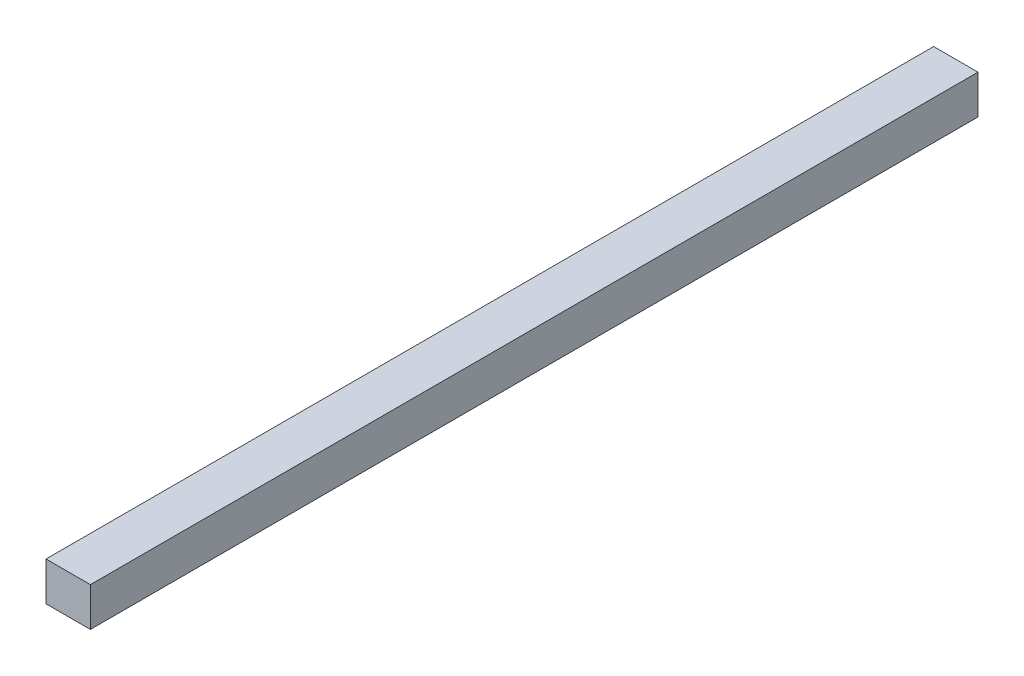
SolidWorks part; units mm, degrees
ref_plane "Front Plane" through (0, 0, 0) normal (0, 0, 1) x (1, 0, 0)
ref_plane "Top Plane" through (0, 0, 0) normal (0, 1, 0) x (1, 0, 0)
ref_plane "Right Plane" through (0, 0, 0) normal (1, 0, 0) x (0, 0, -1)
sketch "Sketch1" plane through (0, 0, 0) normal (0, 1, 0) x (1, 0, 0)
  line L1 (32.4965, 34.4965) -> (34.4965, 34.4965)
  line L2 (32.4965, 34.4965) -> (32.4965, -5.5035)
  line L3 (32.4965, -5.5035) -> (34.4965, -5.5035)
  line L4 (34.4965, 34.4965) -> (34.4965, -5.5035)
  dimension "D1" = 40
  dimension "D2" = 2
extrude "Boss-Extrude1" add sketch "Sketch1" along normal blind 1.75
scale "Scale1" scale about centroid uniform scaling yes scale factor 10
